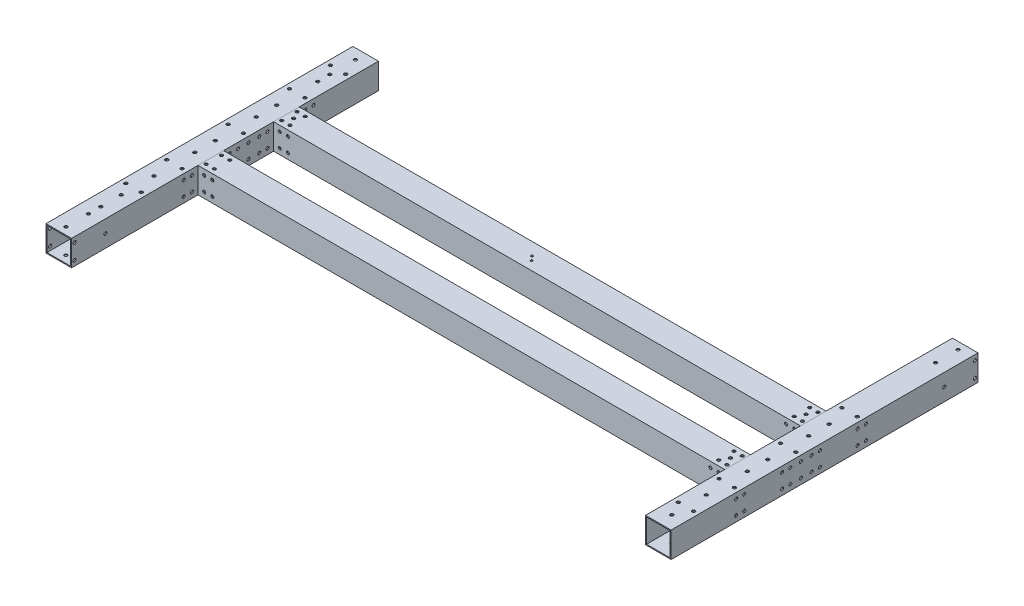
SolidWorks part; units mm, degrees
material "6061 合金"
ref_plane "前视基准面" through (0, 0, 0) normal (0, 0, 1) x (1, 0, 0)
ref_plane "上视基准面" through (0, 0, 0) normal (0, 1, 0) x (1, 0, 0)
ref_plane "右视基准面" through (0, 0, 0) normal (1, 0, 0) x (0, 0, -1)
sketch3d "3D草图1"
  line L0 (0, 0, 136.1) -> (0, 0, -163.9)
  line L1 (0, 0, 0) -> (540, 0, 0)
  line L2 (0, 0, -73.9) -> (540, 0, -73.9)
  line L3 (540, 0, -210) -> (540, 0, 90)
  dimension "D1" = 540
  dimension "D2" = 73.9
  dimension "D4" = 90
  dimension "D3" = 210
  dimension "D5" = 90
other "方形管 20X20X1(1)"
ref_plane "基准面1" through (0, 0, 0) normal (1, 0, 0) x (0, 0, -1)
sketch "草图1" plane through (0, 0, 0) normal (1, 0, 0) x (0, 0, -1)
  line L0 (-11.5, 11.5) -> (11.5, 11.5)
  line L1 (-12.5, 12.5) -> (12.5, 12.5)
  line L2 (-12.5, 12.5) -> (-12.5, -12.5)
  line L3 (-12.5, -12.5) -> (12.5, -12.5)
  line L4 (12.5, 12.5) -> (12.5, -12.5)
  line L5 (-12.5, 12.5) -> (12.5, -12.5) construction
  line L6 (-12.5, -12.5) -> (12.5, 12.5) construction
  line L7 (11.5, 11.5) -> (11.5, -11.5)
  line L8 (-11.5, -11.5) -> (11.5, -11.5)
  line L9 (-11.5, 11.5) -> (-11.5, -11.5)
  point P0 (0, 0)
  point P10 (0, 0)
  dimension "D1" = 25
  dimension "D2" = 1
sketch "草图2" plane through (552.5, 0, 0) normal (1, 0, 0) x (0, 0, -1)
  line L0 (86.4, 12.5) -> (61.4, 12.5) construction
  line L1 (86.4, 12.5) -> (61.4, 12.5) construction
  line L2 (73.9, 12.5) -> (73.9, 0) construction
  line L3 (12.5, -12.5) -> (12.5, 12.5) construction
  line L4 (61.4, 12.5) -> (61.4, -12.5) construction
  line L5 (12.5, -12.5) -> (12.5, 12.5) construction
  line L6 (61.4, 12.5) -> (61.4, -12.5) construction
  line L7 (36.95, 12.5) -> (36.95, -7) construction
  line L8 (210, 12.5) -> (-90, 12.5) construction
  line L9 (0, 0) -> (28.2436, 0) construction
  circle A0 centre (73.9, 0) radius 5 construction
  circle A1 centre (36.95, 7) radius 1.5
  circle A2 centre (36.95, -7) radius 1.5
  circle A3 centre (26.5, 7) radius 1.5
  circle A4 centre (26.5, -7) radius 1.5
  circle A5 centre (47.4, -7) radius 1.5
  circle A6 centre (47.4, 7) radius 1.5
  dimension "D1" = 10
  dimension "D3" = 3
  dimension "D2" = 14
  dimension "D4" = 10.45
extrude "切除-拉伸1" cut sketch "草图2" against normal through all
sketch "草图3" plane through (0, 12.5, 0) normal (0, 1, 0) x (1, 0, 0)
  line L0 (12.5, 0) -> (19.5, 0) construction
  line L1 (12.5, 12.5) -> (12.5, -12.5) construction
  line L2 (12.5, 163.9) -> (12.5, -136.1) construction
  line L3 (23.5, 7.5) -> (15.5, 7.5) construction
  line L4 (23.5, 7.5) -> (23.5, -7.5) construction
  line L5 (23.5, -7.5) -> (15.5, -7.5) construction
  line L6 (15.5, 7.5) -> (15.5, -7.5) construction
  line L7 (23.5, 7.5) -> (15.5, -7.5) construction
  line L8 (23.5, -7.5) -> (15.5, 7.5) construction
  line L9 (12.5, 36.95) -> (32.3531, 36.95) construction
  line L10 (527.5, 12.5) -> (12.5, 12.5) construction
  line L11 (527.5, 61.4) -> (12.5, 61.4) construction
  line L12 (270, -12.5) -> (270, 43.703) construction
  line L13 (527.5, -12.5) -> (12.5, -12.5) construction
  circle A0 centre (15.5, 7.5) radius 1.5
  circle A1 centre (15.5, -7.5) radius 1.5
  circle A2 centre (23.5, -7.5) radius 1.5
  circle A3 centre (23.5, 7.5) radius 1.5
  circle A4 centre (15.5, 66.4) radius 1.5
  circle A5 centre (23.5, 66.4) radius 1.5
  circle A6 centre (23.5, 81.4) radius 1.5
  circle A7 centre (15.5, 81.4) radius 1.5
  circle A8 centre (524.5, 7.5) radius 1.5
  circle A9 centre (516.5, 7.5) radius 1.5
  circle A10 centre (516.5, -7.5) radius 1.5
  circle A11 centre (524.5, -7.5) radius 1.5
  circle A12 centre (524.5, 81.4) radius 1.5
  circle A13 centre (516.5, 81.4) radius 1.5
  circle A14 centre (516.5, 66.4) radius 1.5
  circle A15 centre (524.5, 66.4) radius 1.5
  dimension "D4" = 3
  dimension "D1" = 8
  dimension "D2" = 3
  dimension "D3" = 15
extrude "切除-拉伸2" cut sketch "草图3" against normal through all and the other way through all
sketch "草图4" plane through (0, 12.5, 0) normal (0, 1, 0) x (1, 0, 0)
  line L0 (-11.5, -136.1) -> (11.5, -136.1) construction
  line L1 (0, -136.1) -> (0, -129.1) construction
  line L2 (-12.5, -136.1) -> (12.5, -136.1) construction
  line L3 (12.5, 163.9) -> (12.5, -136.1) construction
  line L4 (-12.5, 163.9) -> (12.5, 163.9) construction
  line L5 (12.5, 36.95) -> (35.653, 36.95) construction
  circle A0 centre (0, -75) radius 1.55
  circle A1 centre (0, -95) radius 1.55
  circle A2 centre (0, 153.9) radius 1.55
  circle A3 centre (0, 128.9) radius 1.55
  circle A4 centre (15.5, 66.4) radius 1.5 construction
  circle A5 centre (15.5, 7.5) radius 1.5 construction
  circle A6 centre (19.5, 73.9074) radius 1.55 construction
  circle A7 centre (0, 116.95) radius 1.55
  circle A8 centre (7.5, 136.9) radius 1.55
  circle A11 centre (19.5, 73.9074) radius 1.55
  circle A14 centre (-7.5, -63) radius 1.55 construction
  circle A15 centre (7.5, -63) radius 1.55 construction
  circle A16 centre (0, -43.05) radius 1.55 construction
  circle A17 centre (-7.5, -23.05) radius 1.55 construction
  circle A18 centre (7.5, -23.05) radius 1.55 construction
  circle A19 centre (0, -3.05) radius 1.55 construction
  circle A20 centre (0, 16.95) radius 1.55 construction
  circle A21 centre (-7.5, 36.95) radius 1.55 construction
  circle A22 centre (7.5, 36.95) radius 1.55 construction
  circle A23 centre (0, 56.95) radius 1.55 construction
  circle A24 centre (0, 76.95) radius 1.55 construction
  circle A25 centre (-7.5, 96.95) radius 1.55 construction
  circle A26 centre (7.5, 96.95) radius 1.55 construction
  circle A27 centre (-7.5, -63) radius 1.55
  circle A28 centre (7.5, -63) radius 1.55
  circle A29 centre (0, -43.05) radius 1.55
  circle A30 centre (-7.5, -23.05) radius 1.55
  circle A31 centre (7.5, -23.05) radius 1.55
  circle A32 centre (0, -3.05) radius 1.55
  circle A33 centre (0, 16.95) radius 1.55
  circle A34 centre (-7.5, 36.95) radius 1.55
  circle A35 centre (7.5, 36.95) radius 1.55
  circle A36 centre (0, 56.95) radius 1.55
  circle A37 centre (0, 76.95) radius 1.55
  circle A38 centre (-7.5, 96.95) radius 1.55
  circle A39 centre (7.5, 96.95) radius 1.55
  circle A40 centre (-7.5, 136.9) radius 1.55
  circle A52 centre (0, -129.1) radius 1.55
  circle A53 centre (0, -107.1) radius 1.55
  circle A54 centre (532.5, -63) radius 1.55 construction
  circle A55 centre (547.5, -63) radius 1.55 construction
  circle A56 centre (540, -43.05) radius 1.55 construction
  circle A57 centre (532.5, -23.05) radius 1.55 construction
  circle A58 centre (547.5, -23.05) radius 1.55 construction
  circle A59 centre (540, -3.05) radius 1.55 construction
  circle A60 centre (540, 16.95) radius 1.55 construction
  circle A61 centre (532.5, 36.95) radius 1.55 construction
  circle A62 centre (547.5, 36.95) radius 1.55 construction
  circle A63 centre (540, 56.95) radius 1.55 construction
  circle A64 centre (540, 76.95) radius 1.55 construction
  circle A65 centre (547.5, 96.95) radius 1.55 construction
  circle A66 centre (532.5, 96.95) radius 1.55 construction
  circle A67 centre (520.5, 0) radius 1.55 construction
  circle A68 centre (520.5, 73.9074) radius 1.55 construction
  circle A69 centre (532.5, -63) radius 1.55
  circle A70 centre (547.5, -63) radius 1.55
  circle A71 centre (540, -43.05) radius 1.55
  circle A72 centre (532.5, -23.05) radius 1.55
  circle A73 centre (547.5, -23.05) radius 1.55
  circle A74 centre (540, -3.05) radius 1.55
  circle A75 centre (540, 16.95) radius 1.55
  circle A76 centre (532.5, 36.95) radius 1.55
  circle A77 centre (547.5, 36.95) radius 1.55
  circle A78 centre (540, 56.95) radius 1.55
  circle A79 centre (540, 76.95) radius 1.55
  circle A80 centre (547.5, 96.95) radius 1.55
  circle A81 centre (532.5, 96.95) radius 1.55
  circle A82 centre (520.5, 0) radius 1.55
  circle A83 centre (520.5, 73.9074) radius 1.55
  circle A86 centre (540, -76.8) radius 1.55
  circle A87 centre (540, -94.8) radius 1.55
  circle A90 centre (539.975, 181) radius 1.55
  circle A91 centre (539.975, 203) radius 1.55
  dimension "D1" = 22
  dimension "D3" = 3.1
  dimension "D6" = 3.1
  dimension "D2" = 7
  dimension "D4" = 25
  dimension "D5" = 10
  dimension "D7" = 12
  dimension "D8" = 20
sketch "草图5" plane through (552.5, 0, 0) normal (1, 0, 0) x (0, 0, -1)
  line L0 (210, 12.5) -> (210, -12.5) construction
  line L1 (210, 0) -> (203.0323, 0) construction
  line L2 (-136.1, 12.5) -> (-136.1, -12.5) construction
  line L3 (-136.1, 0) -> (-124.4955, 0) construction
  circle A2 centre (207, 7.5) radius 1.55
  circle A3 centre (177, 0) radius 1.55
  circle A6 centre (-103.1, 0) radius 1.55
  circle A7 centre (-133.1, 7.5) radius 1.55
  circle A8 centre (-133.1, -7.5) radius 1.55
  circle A9 centre (207, -7.5) radius 1.55
  dimension "D4" = 3.1
  dimension "D6" = 3.1
  dimension "D8" = 30
  dimension "D1" = 3
  dimension "D2" = 3
  dimension "D3" = 15
  dimension "D5" = 15
  dimension "D7" = 30
extrude "切除-拉伸3" cut sketch "草图4" against normal through all
sketch "草图6" plane through (0, 0, -86.4) normal (0, 0, -1) x (-1, 0, 0)
  line L0 (-270, 12.5) -> (-270, -51.8847) construction
  line L1 (-527.5, 12.5) -> (-12.5, 12.5) construction
  circle A0 centre (-26.5, -7) radius 1.5 construction
  circle A1 centre (-18.5, -7) radius 1.5 construction
  circle A2 centre (-18.5, 7) radius 1.5 construction
  circle A3 centre (-26.5, 7) radius 1.5 construction
  circle A4 centre (-26.5, -7) radius 1.5
  circle A5 centre (-18.5, -7) radius 1.5
  circle A6 centre (-18.5, 7) radius 1.5
  circle A7 centre (-26.5, 7) radius 1.5
  circle A8 centre (-513.5, 7) radius 1.5
  circle A9 centre (-521.5, 7) radius 1.5
  circle A10 centre (-521.5, -7) radius 1.5
  circle A11 centre (-513.5, -7) radius 1.5
extrude "切除-拉伸4" cut sketch "草图5" against normal through all
extrude "切除-拉伸5" cut sketch "草图6" against normal through all
sketch "草图7" plane through (0, 12.5, 0) normal (0, 1, 0) x (1, 0, 0)
  line L0 (527.5, 86.4) -> (12.5, 86.4) construction
  line L1 (12.5, 163.9) -> (12.5, -136.1) construction
  circle A0 centre (256.1883, 69.99) radius 1.05
  circle A1 centre (252.5, 74.07) radius 1.05
  dimension "D2" = 2.1
  dimension "D1" = 5.5
  dimension "D3" = 16.41
  dimension "D4" = 12.33
  dimension "D5" = 240
extrude "切除-拉伸6" cut sketch "草图7" against normal through all
sketch "草图8" plane through (12.5, 0, 0) normal (1, 0, 0) x (0, 0, -1)
  line L0 (73.9074, -12.5) -> (73.9074, 21.1624) construction
  line L1 (36.95, 7) -> (36.95, -7) construction
  line L2 (72.3574, -12.5) -> (75.4574, -12.5) construction
  line L3 (72.3574, -12.5) -> (75.4574, -12.5) construction
  circle A0 centre (100.4, -7) radius 1.5 construction
  circle A1 centre (92.4, -7) radius 1.5 construction
  circle A2 centre (100.4, -7) radius 1.5
  circle A3 centre (92.4, -7) radius 1.5
  circle A4 centre (100.4, 7) radius 1.5 construction
  circle A5 centre (92.4, 7) radius 1.5 construction
  circle A6 centre (100.4, 7) radius 1.5
  circle A7 centre (92.4, 7) radius 1.5
  circle A8 centre (55.4147, 7) radius 1.5
  circle A10 centre (55.4147, -7) radius 1.5
  circle A13 centre (18.4853, -7) radius 1.5
  circle A14 centre (18.4853, 7) radius 1.5
  circle A15 centre (-18.5, 7) radius 1.5
  circle A16 centre (-26.5, 7) radius 1.5
  circle A17 centre (-18.5, -7) radius 1.5
  circle A18 centre (-26.5, -7) radius 1.5
extrude "切除-拉伸7" cut sketch "草图8" against normal through all and the other way through all
